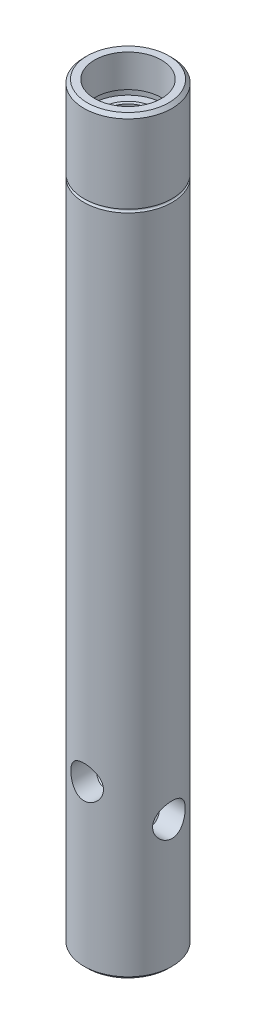
SolidWorks part; units mm, degrees
ref_plane "Плоскость1" through (0, 0, 0) normal (0, 0, 1) x (1, 0, 0)
ref_plane "Плоскость2" through (0, 0, 0) normal (0, 1, 0) x (1, 0, 0)
ref_plane "Плоскость3" through (0, 0, 0) normal (1, 0, 0) x (0, 0, -1)
sketch "Эскиз1" plane through (0, 0, 0) normal (0, 0, 1) x (1, 0, 0)
  line L0 (0, 0) -> (0, 271.3143) construction
  line L1 (13.5, 0) -> (13.5, 204)
  line L2 (13.5, 0) -> (0, 0)
  line L4 (10.25, 230) -> (10.25, 218)
  line L5 (10.25, 218) -> (7, 218)
  line L6 (7, 218) -> (7, 24.0415)
  line L7 (7, 24.0415) -> (0, 20)
  line L8 (13.5, 205) -> (13.5, 230)
  line L9 (0, 0) -> (0, 20)
  line L18 (10.25, 230) -> (13.5, 230)
  arc A0 (13.5, 205) -> (13.5, 204) centre (13.5, 204.5) ccw
  dimension "D8" = 1
  dimension "D9" = 25
  dimension "D1" = 230
  dimension "D2" = 27
  dimension "D3" = 20.5
  dimension "D4" = 20
  dimension "D5" = 14
  dimension "D6" = 12
  dimension "D7" = 60
revolve "Повернуть1" add sketch "Эскиз1" angle 360 about L0
cosmetic thread "Условное изображение резьбы2" parameters "D2"=22
cosmetic thread "Условное изображение резьбы3" parameters "D1"=35, "D2"=25.5
sketch "Эскиз5" plane through (0, 218, 0) normal (0, 1, 0) x (1, 0, 0)
  circle A0 centre (0, 0) radius 8
  circle A1 centre (0, 0) radius 7
extrude "Вытянуть1" add sketch "Эскиз5" along normal blind 0.5
chamfer "Фаска2" distance 1 angle 45 1 edges at (0, 230, -13.5)
sketch "Эскиз6" plane through (0, 218, 0) normal (0, 1, 0) x (1, 0, 0)
  circle A0 centre (0, 0) radius 11
  circle A1 centre (0, 0) radius 10.25
  circle A2 centre (0, 0) radius 10.25 construction
  dimension "D1" = 22
extrude "Вытянуть2" cut sketch "Эскиз6" along normal blind 2
chamfer "Фаска3" distance 1 angle 45 1 edges at (0, 0, -13.5)
ref_plane "Плоскость4" through (13.5, 0, 0) normal (1, 0, 0) x (0, 0, -1)
sketch "Эскиз9" plane through (13.5, 0, 0) normal (1, 0, 0) x (0, 0, -1)
  circle A0 centre (0, 40) radius 5
  dimension "D1" = 10
  dimension "D2" = 40
extrude "Вытянуть3" cut sketch "Эскиз9" against normal through all
ref_plane "Плоскость5" through (0, 0, 13.5) normal (0, 0, 1) x (1, 0, 0)
sketch "Эскиз10" plane through (0, 0, 13.5) normal (0, 0, 1) x (1, 0, 0)
  circle A0 centre (0, 50) radius 5
  dimension "D2" = 10
  dimension "D1" = 50
extrude "Вытянуть4" cut sketch "Эскиз10" against normal through all
